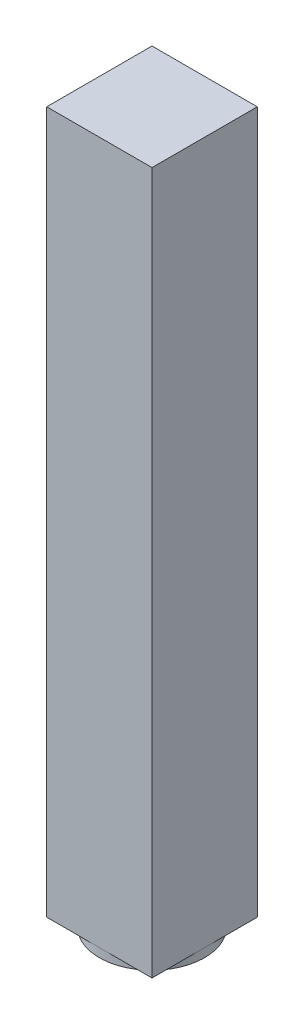
SolidWorks part; units mm, degrees
ref_plane "前视基准面" through (0, 0, 0) normal (0, 0, 1) x (1, 0, 0)
ref_plane "上视基准面" through (0, 0, 0) normal (0, 1, 0) x (1, 0, 0)
ref_plane "右视基准面" through (0, 0, 0) normal (1, 0, 0) x (0, 0, -1)
other "Configuration Table"
sketch "草图1" plane through (0, 0, 0) normal (0, 1, 0) x (1, 0, 0)
  line L1 (-30, -30) -> (30, -30)
  line L2 (-30, -30) -> (-30, 30)
  line L3 (-30, 30) -> (30, 30)
  line L4 (30, -30) -> (30, 30)
  line L5 (-30, -30) -> (30, 30) construction
  line L6 (-30, 30) -> (30, -30) construction
  point P0 (0, 0)
  dimension "D1" = 60
  dimension "D2" = 60
extrude "凸台-拉伸1" add sketch "草图1" along normal blind 400
sketch "草图2" plane through (0, 0, 0) normal (0, -1, 0) x (1, 0, 0)
  circle A0 centre (0, 0) radius 30
  dimension "D1" = 60
extrude "凸台-拉伸2" add sketch "草图2" along normal blind 5
